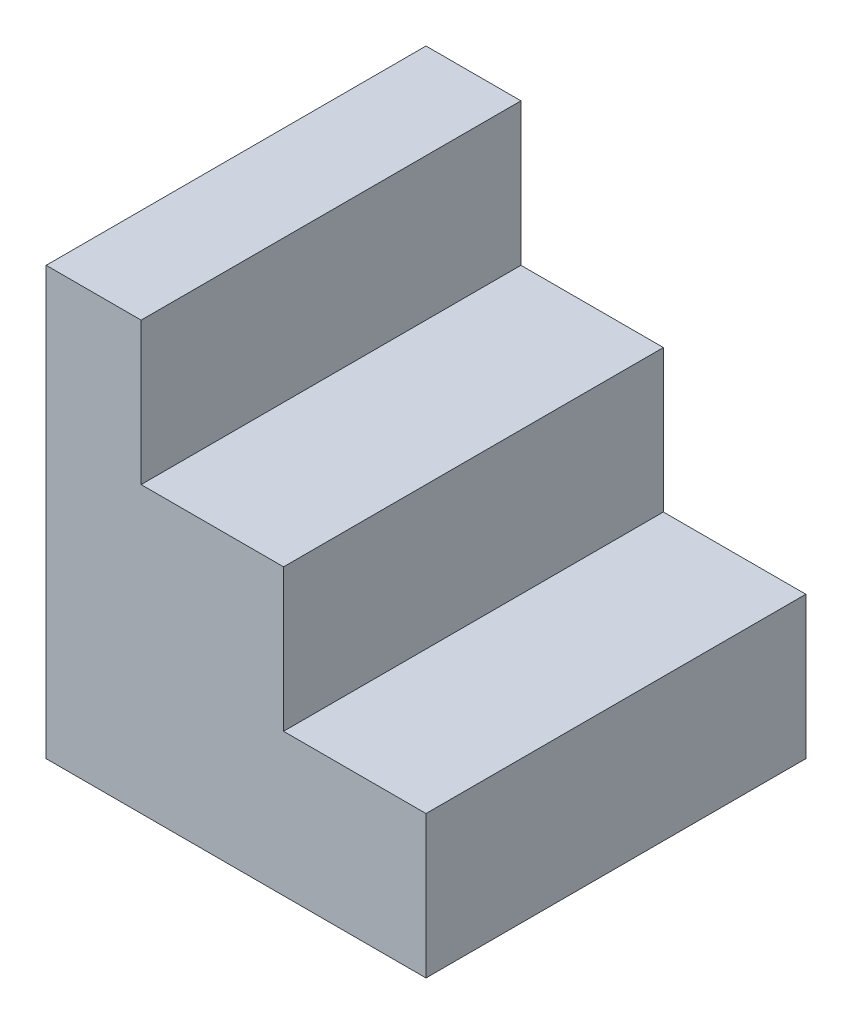
SolidWorks part; units mm, degrees
ref_plane "前基準面" through (0, 0, 0) normal (0, 0, 1) x (1, 0, 0)
ref_plane "上基準面" through (0, 0, 0) normal (0, 1, 0) x (1, 0, 0)
ref_plane "右基準面" through (0, 0, 0) normal (1, 0, 0) x (0, 0, -1)
sketch "草圖1" plane through (0, 0, 0) normal (0, 1, 0) x (1, 0, 0)
  line L1 (-20, 20) -> (20, 20)
  line L2 (-20, 20) -> (-20, -20)
  line L3 (-20, -20) -> (20, -20)
  line L4 (20, 20) -> (20, -20)
  line L5 (-20, 20) -> (20, -20) construction
  line L6 (-20, -20) -> (20, 20) construction
  point P0 (0, 0)
  point P5 (0, 0)
  dimension "D1" = 40
  dimension "D2" = 40
extrude "填料-伸長1" add sketch "草圖1" along normal blind 15
sketch "草圖2" plane through (0, 15, 0) normal (0, 1, 0) x (1, 0, 0)
  line L0 (-20, -20) -> (20, -20) construction
  line L1 (-20, 20) -> (5, 20)
  line L2 (-20, 20) -> (-20, -20)
  line L3 (-20, -20) -> (5, -20)
  line L4 (5, 20) -> (5, -20)
  dimension "D1" = 15
extrude "填料-伸長2" add sketch "草圖2" along normal blind 15
sketch "草圖3" plane through (0, 30, 0) normal (0, 1, 0) x (1, 0, 0)
  line L0 (-20, -20) -> (5, -20) construction
  line L1 (-20, 20) -> (-10, 20)
  line L2 (-20, 20) -> (-20, -20)
  line L3 (-20, -20) -> (-10, -20)
  line L4 (-10, 20) -> (-10, -20)
  dimension "D1" = 15
extrude "填料-伸長3" add sketch "草圖3" along normal blind 15
